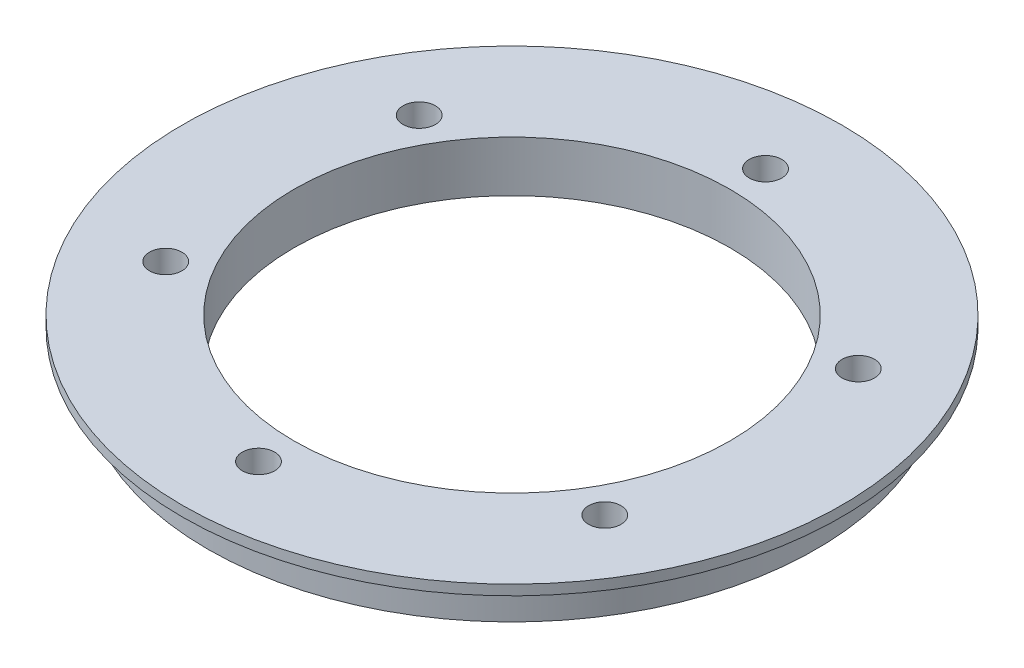
SolidWorks part; units mm, degrees
ref_plane "Front Plane" through (0, 0, 0) normal (0, 0, 1) x (1, 0, 0)
ref_plane "Top Plane" through (0, 0, 0) normal (0, 1, 0) x (1, 0, 0)
ref_plane "Right Plane" through (0, 0, 0) normal (1, 0, 0) x (0, 0, -1)
sketch "Sketch1" plane through (0, 0, 0) normal (0, 1, 0) x (1, 0, 0)
  circle A0 centre (0, 0) radius 30
  circle A2 centre (0, 0) radius 25 construction
  dimension "D1" = 60
  dimension "D2" = 50
extrude "Boss-Extrude1" add sketch "Sketch1" along normal blind 5
sketch "Sketch2" plane through (0, 5, 0) normal (0, 1, 0) x (1, 0, 0)
  circle A0 centre (0, 0) radius 32.5
  dimension "D1" = 65
extrude "Boss-Extrude2" add sketch "Sketch2" against normal blind 1
sketch "Sketch3" plane through (0, 0, 0) normal (0, -1, 0) x (1, 0, 0)
  circle A0 centre (0, 0) radius 21.5
  dimension "D1" = 43
extrude "Cut-Extrude1" cut sketch "Sketch3" against normal blind 25
sketch "Sketch4" plane through (0, 5, 0) normal (0, 1, 0) x (1, 0, 0)
  circle A0 centre (0, 0) radius 25 construction
  circle A1 centre (0, 25) radius 1.6
  circle A2 centre (0, 0) radius 25 construction
  circle A3 centre (21.6506, 12.5) radius 1.6
  circle A4 centre (0, 0) radius 25 construction
  circle A5 centre (21.6506, -12.5) radius 1.6
  circle A6 centre (0, 0) radius 25 construction
  circle A7 centre (0, -25) radius 1.6
  circle A8 centre (0, 0) radius 25 construction
  circle A9 centre (-21.6506, -12.5) radius 1.6
  circle A10 centre (0, 0) radius 25 construction
  circle A11 centre (-21.6506, 12.5) radius 1.6
  point P22 (0, 0)
  dimension "D1" = 50
  dimension "D2" = 3.2
  dimension "D3" = 6
extrude "Cut-Extrude2" cut sketch "Sketch4" against normal blind 25
